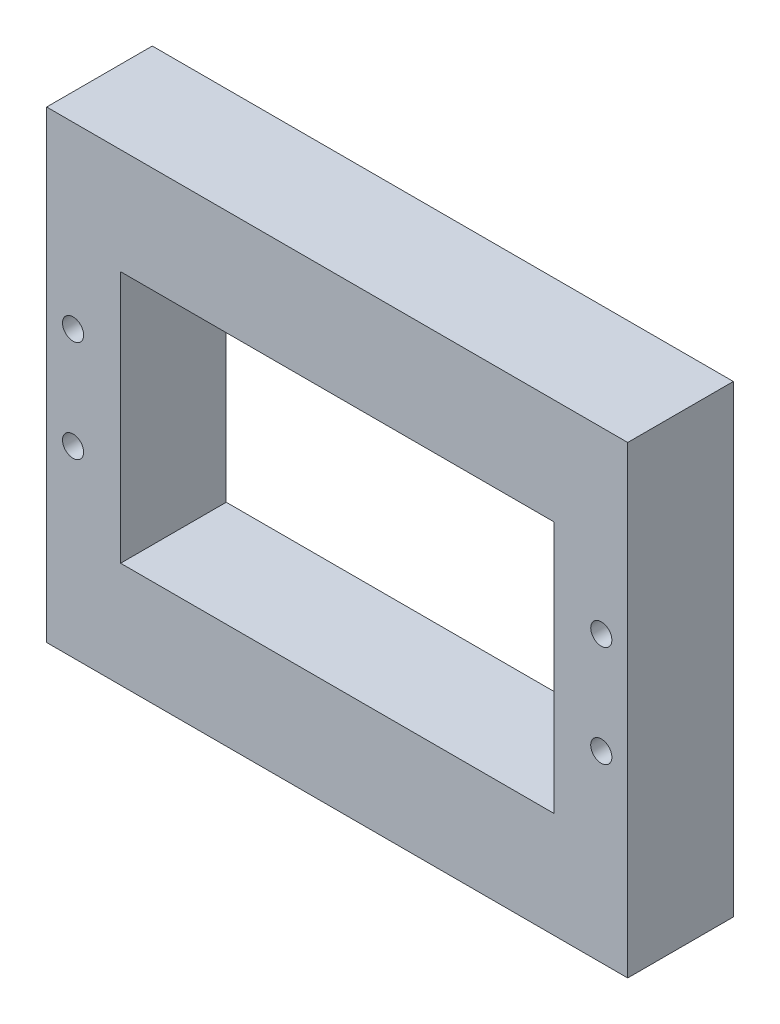
SolidWorks part; units mm, degrees
ref_plane "Front Plane" through (0, 0, 0) normal (0, 0, 1) x (1, 0, 0)
ref_plane "Top Plane" through (0, 0, 0) normal (0, 1, 0) x (1, 0, 0)
ref_plane "Right Plane" through (0, 0, 0) normal (1, 0, 0) x (0, 0, -1)
sketch "Sketch1" plane through (0, 0, 0) normal (0, 1, 0) x (1, 0, 0)
  line L1 (0, 0) -> (55, 0)
  line L2 (0, 0) -> (0, 10)
  line L3 (0, 10) -> (55, 10)
  line L4 (55, 0) -> (55, 10)
  dimension "D1" = 55
  dimension "D2" = 10
extrude "Boss-Extrude1" add sketch "Sketch1" along normal blind 1
sketch "Sketch2" plane through (0, 1, 0) normal (0, 1, 0) x (1, 0, 0)
  line L0 (27.5, 10) -> (27.5, 0) construction
  line L1 (55, 10) -> (0, 10) construction
  line L2 (0, 0) -> (55, 0) construction
  line L3 (48, 10) -> (48, 0) construction
  line L4 (0, 5) -> (55, 5) construction
  line L5 (0, 10) -> (0, 0) construction
  line L6 (55, 0) -> (55, 10) construction
  line L7 (55, 0) -> (55, 10)
  line L8 (55, 10) -> (48, 10)
  line L9 (48, 10) -> (48, 0)
  line L10 (48, 0) -> (55, 0)
  line L11 (7, 10) -> (7, 0)
  line L12 (0, 10) -> (7, 10)
  line L13 (0, 0) -> (0, 10)
  line L14 (7, 0) -> (0, 0)
  point P6 (48, 10)
  point P16 (55, 0)
  dimension "D1" = 7
  dimension "D2" = 10
  dimension "D3" = 10
extrude "Boss-Extrude2" add sketch "Sketch2" along normal blind 23.9
sketch "Sketch4" plane through (0, 0, 0) normal (0, 0, 1) x (1, 0, 0)
  line L0 (27.5, 1) -> (27.5, 32.1935) construction
  line L1 (0, 24.9) -> (0, 3.6) construction
  line L2 (0, 24.9) -> (0, 0) construction
  line L3 (0, 3.6) -> (7, 24.9) construction
  line L4 (2.4488, 13.15) -> (-6.0255, 13.15) construction
  circle A0 centre (2.5, 17.95) radius 1
  circle A1 centre (2.5, 8.35) radius 1
  circle A2 centre (52.5, 8.35) radius 1
  circle A3 centre (52.5, 17.95) radius 1
  dimension "D3" = 2.5
  dimension "D4" = 2
  dimension "D1" = 21.3
  dimension "D2" = 4.8
extrude "Cut-Extrude2" cut sketch "Sketch4" against normal up to next
sketch "Sketch5" plane through (0, 0, 0) normal (0, -1, 0) x (1, 0, 0)
  line L1 (0, 0) -> (55, 0)
  line L2 (0, 0) -> (0, -10)
  line L3 (0, -10) -> (55, -10)
  line L4 (55, 0) -> (55, -10)
extrude "Boss-Extrude3" add sketch "Sketch5" along normal blind 9
sketch "Sketch6" plane through (0, 24.9, 0) normal (0, 1, 0) x (1, 0, 0)
  line L1 (0, 10) -> (55, 10)
  line L2 (0, 10) -> (0, 0)
  line L3 (0, 0) -> (55, 0)
  line L4 (55, 10) -> (55, 0)
extrude "Boss-Extrude4" add sketch "Sketch6" along normal blind 10
